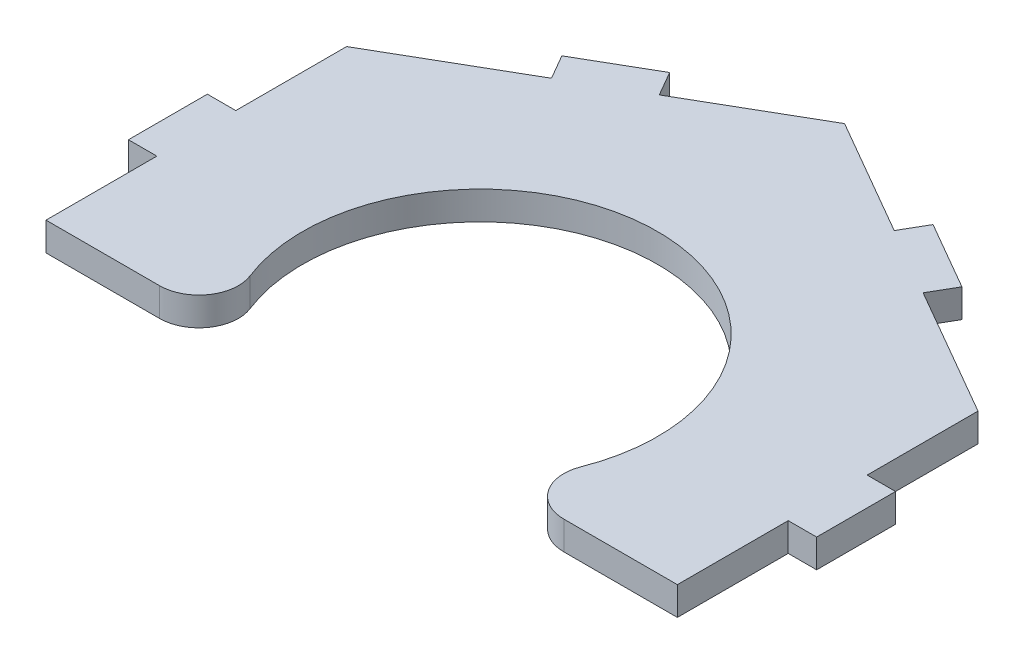
SolidWorks part; units mm, degrees
ref_plane "Front Plane" through (0, 0, 0) normal (0, 0, 1) x (1, 0, 0)
ref_plane "Top Plane" through (0, 0, 0) normal (0, 1, 0) x (1, 0, 0)
ref_plane "Right Plane" through (0, 0, 0) normal (1, 0, 0) x (0, 0, -1)
sketch "Sketch1" plane through (0, 0, 0) normal (0, 1, 0) x (1, 0, 0)
  line L0 (-50.8, -19.05) -> (-32.5341, -19.05)
  line L1 (50.8, -19.05) -> (50.8, 29.3294)
  line L2 (50.8, 29.3294) -> (0, 58.6588)
  line L3 (0, 58.6588) -> (-50.8, 29.3294)
  line L4 (-50.8, 29.3294) -> (-50.8, -19.05)
  line L7 (-25.4, -43.9941) -> (-9.8224, -52.9878) [skipped]
  line L8 (25.4, -43.9941) -> (40.9776, -35.0003) [skipped]
  line L9 (50.8, -19.05) -> (32.5341, -19.05)
  arc A0 (50.8, 0) -> (-50.8, 0) centre (0, 0) ccw construction
  arc A1 (26.6188, -10.3909) -> (-26.6188, -10.3909) centre (0, 0) ccw
  arc A2 (32.5341, -19.05) -> (26.6188, -10.3909) centre (32.5341, -12.7) cw
  arc A3 (-32.5341, -19.05) -> (-26.6188, -10.3909) centre (-32.5341, -12.7) ccw
  point P8 (-36.1544, 20.8738)
  dimension "D1" = 28.575
  dimension "D2" = 50.8
  dimension "D4" = 6.35
  dimension "D3" = 19.05
extrude "Boss-Extrude1" add sketch "Sketch1" along normal blind 4.572
sketch "Sketch2" plane through (0, 4.572, 0) normal (0, 1, 0) x (1, 0, 0)
  line L0 (-50.8, 11.4897) -> (-55.372, 11.4897)
  line L1 (-50.8, 29.3294) -> (-50.8, -19.05) construction
  line L2 (-55.372, 11.4897) -> (-55.372, -1.2103)
  line L3 (-55.372, -1.2103) -> (-50.8, -1.2103)
  line L4 (-29.9028, 41.3944) -> (-32.1888, 45.3539)
  line L5 (0, 58.6588) -> (-50.8, 29.3294) construction
  line L6 (-32.1888, 45.3539) -> (-21.1903, 51.7039)
  line L7 (-21.1903, 51.7039) -> (-18.9043, 47.7444)
  line L8 (18.9043, 47.7444) -> (21.1903, 51.7039)
  line L9 (50.8, 29.3294) -> (0, 58.6588) construction
  line L10 (21.1903, 51.7039) -> (32.1888, 45.3539)
  line L11 (32.1888, 45.3539) -> (29.9028, 41.3944)
  line L13 (50.8, 11.4897) -> (55.372, 11.4897)
  line L14 (50.8, -19.05) -> (50.8, 29.3294) construction
  line L15 (55.372, 11.4897) -> (55.372, -1.2103)
  line L16 (55.372, -1.2103) -> (50.8, -1.2103)
  line L20 (-50.8, -1.2103) -> (-50.8, 11.4897)
  line L21 (-29.9028, 41.3944) -> (-18.9043, 47.7444)
  line L22 (18.9043, 47.7444) -> (29.9028, 41.3944)
  line L23 (50.8, 11.4897) -> (50.8, -1.2103)
  point P24 (-50.8, 5.1397)
  point P25 (-55.372, 5.1397)
  point P26 (55.372, 5.1397)
  dimension "D1" = 24.13
  dimension "D2" = 24.13
  dimension "D3" = 12.7
  dimension "D4" = 4.572
extrude "Boss-Extrude2" add sketch "Sketch2" against normal blind 4.572
